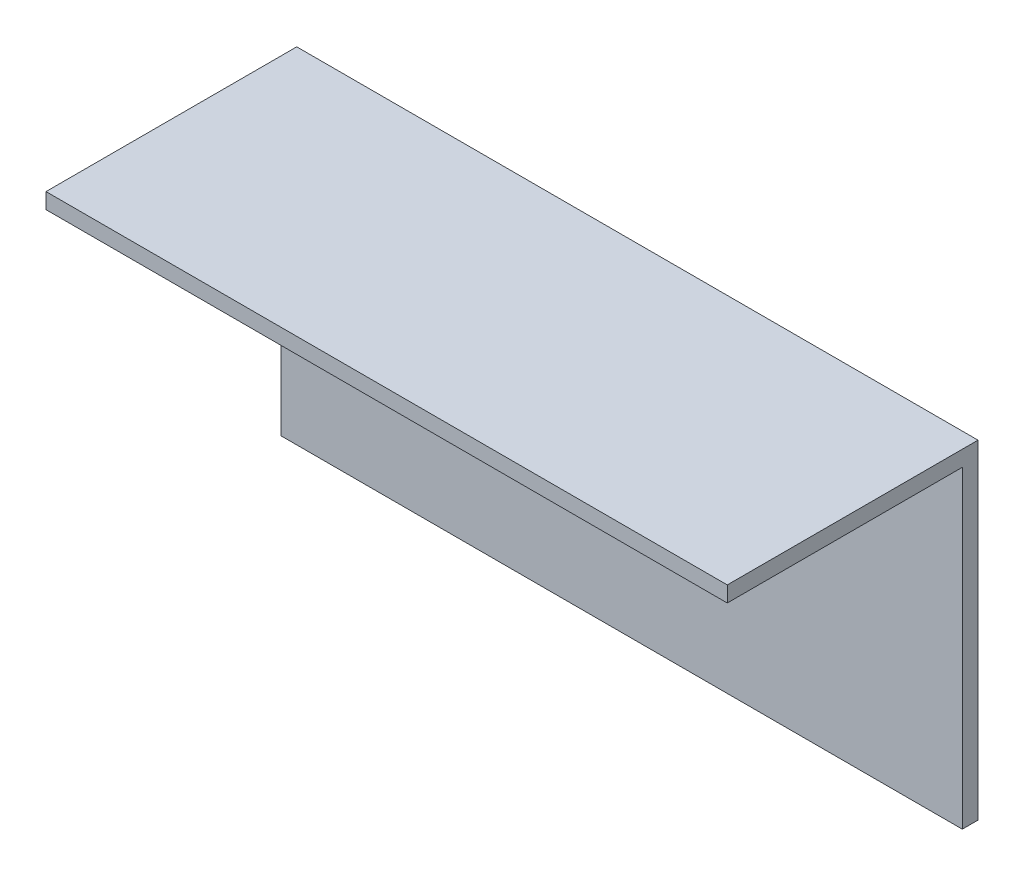
SolidWorks part; units mm, degrees
ref_plane "Alzado" through (0, 0, 0) normal (0, 0, 1) x (1, 0, 0)
ref_plane "Planta" through (0, 0, 0) normal (0, 1, 0) x (1, 0, 0)
ref_plane "Vista lateral" through (0, 0, 0) normal (1, 0, 0) x (0, 0, -1)
sketch "Croquis1" plane through (0, 0, 0) normal (0, 0, 1) x (1, 0, 0)
  line L1 (-217.37, -105) -> (217.37, -105)
  line L2 (-217.37, -105) -> (-217.37, 105)
  line L3 (-217.37, 105) -> (217.37, 105)
  line L4 (217.37, -105) -> (217.37, 105)
  line L5 (-217.37, -105) -> (217.37, 105) construction
  line L6 (-217.37, 105) -> (217.37, -105) construction
  point P0 (0, 0)
  dimension "D1" = 210
  dimension "D3" = 434.74
extrude "Saliente-Extruir1" add sketch "Croquis1" along normal blind 10
sketch "Croquis2" plane through (0, 0, 10) normal (0, 0, 1) x (1, 0, 0)
  line L0 (217.37, -105) -> (217.37, 105) construction
  line L1 (-217.37, 105) -> (217.37, 105)
  line L2 (-217.37, 105) -> (-217.37, 95)
  line L3 (-217.37, 95) -> (217.37, 95)
  line L4 (217.37, 105) -> (217.37, 95)
  dimension "D1" = 10
extrude "Saliente-Extruir2" add sketch "Croquis2" along normal blind 150
